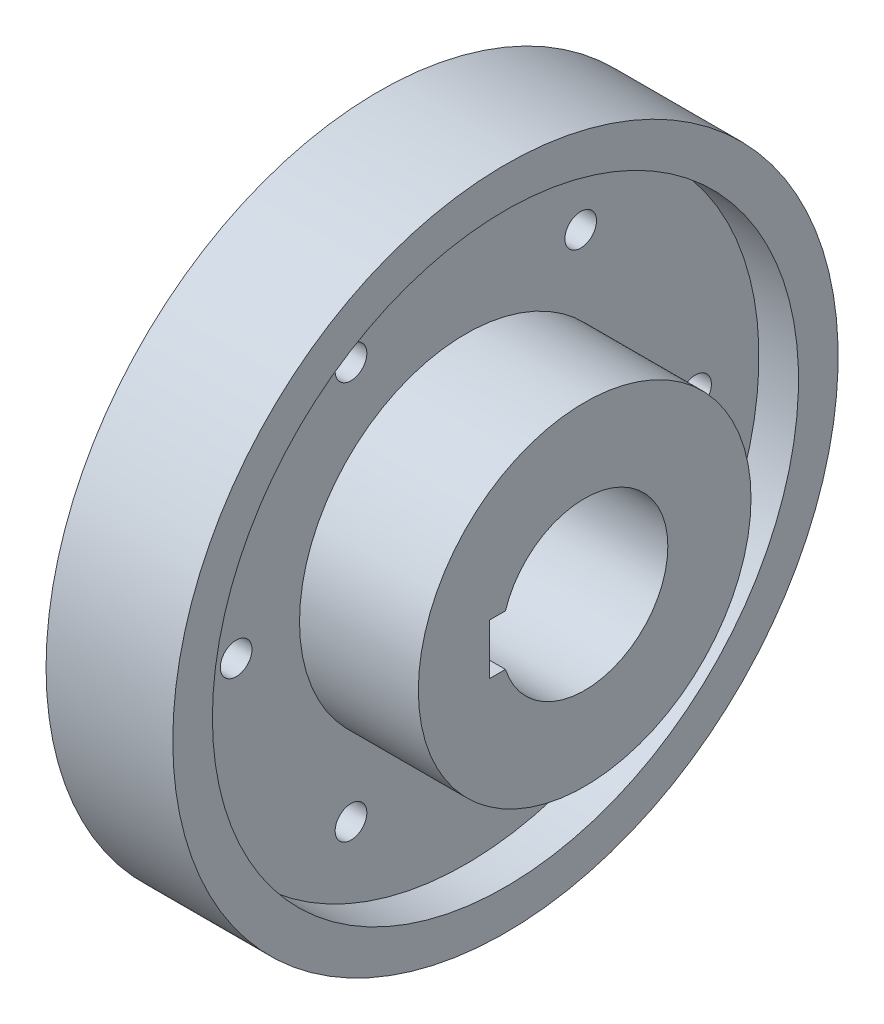
SolidWorks part; units mm, degrees
material "Malleable Cast Iron"
ref_plane "Front Plane" through (0, 0, 0) normal (1, 0, 0) x (0, 1, 0)
ref_plane "Top Plane" through (0, 0, 0) normal (0, 0, 1) x (0, 1, 0)
ref_plane "Right Plane" through (0, 0, 0) normal (0, 1, 0) x (-1, 0, 0)
sketch "Sketch2" plane through (0, 0, 0) normal (0, 1, 0) x (-1, 0, 0)
  line L0 (-138.4348, 52.5) -> (-268.4348, 52.5)
  line L1 (-268.4348, 52.5) -> (-268.4348, 105)
  line L2 (-268.4348, 105) -> (-193.4348, 105)
  line L3 (-193.4348, 105) -> (-193.4348, 185)
  line L4 (-193.4348, 185) -> (-218.4348, 185)
  line L5 (-218.4348, 185) -> (-218.4348, 210)
  line L6 (-218.4348, 210) -> (-138.4348, 210)
  line L7 (-138.4348, 210) -> (-138.4348, 52.5)
  line L8 (0, 0) -> (-419.8736, 0) construction
  dimension "D1" = 105
  dimension "D2" = 25
  dimension "D3" = 210
  dimension "D4" = 55
  dimension "D5" = 80
  dimension "D6" = 50
  dimension "D7" = 52.5
revolve "Revolve1" add sketch "Sketch2" angle 360 about L8
sketch "Sketch3" plane through (193.4348, 0, 0) normal (1, 0, 0) x (0, 1, 0)
  circle A0 centre (0, 0) radius 145 construction
  circle A1 centre (0, 145) radius 10
  dimension "D1" = 290
  dimension "D2" = 20
extrude "Cut-Extrude1" cut sketch "Sketch3" against normal through all
pattern_circular "CirPattern1" count 6 over 360 about axis through (0, 0, 0) along (1, 0, 0) of "Cut-Extrude1"
sketch "Sketch5" plane through (138.4348, 0, 0) normal (-1, 0, 0) x (0, -1, 0)
  circle A0 centre (0, 0) radius 100
  dimension "D1" = 200
extrude "Boss-Extrude1" add sketch "Sketch5" along normal blind 10
sketch "Sketch4" plane through (138.4348, 0, 0) normal (-1, 0, 0) x (0, -1, 0)
  line L1 (-16, 60.0025) -> (16, 60.0025)
  line L2 (-16, 60.0025) -> (-16, 50.0025)
  line L3 (-16, 50.0025) -> (16, 50.0025)
  line L4 (16, 60.0025) -> (16, 50.0025)
  line L5 (-16, 60.0025) -> (16, 50.0025) construction
  line L6 (-16, 50.0025) -> (16, 60.0025) construction
  circle A0 centre (0, 0) radius 52.5 construction
  point P0 (0, 55.0025)
  point P7 (0, 0)
  dimension "D1" = 10
  dimension "D2" = 32
extrude "Cut-Extrude2" cut sketch "Sketch4" against normal through all both and the other way through all
sketch "Sketch6" plane through (128.4348, 0, 0) normal (-1, 0, 0) x (0, -1, 0)
  circle A0 centre (0, 0) radius 52.5
  dimension "D1" = 105
extrude "Cut-Extrude4" cut sketch "Sketch6" against normal through all both and the other way through all
